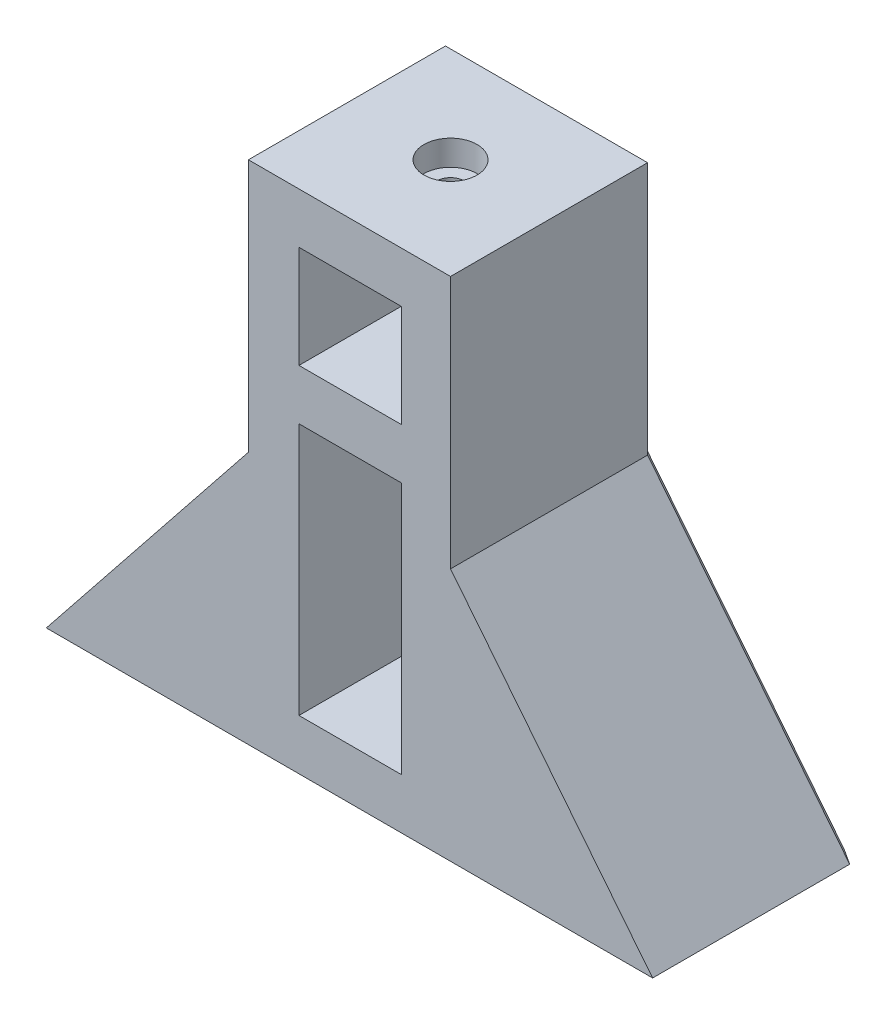
SolidWorks part; units mm, degrees
ref_plane "Front Plane" through (0, 0, 0) normal (0, 0, 1) x (1, 0, 0)
ref_plane "Top Plane" through (0, 0, 0) normal (0, 1, 0) x (1, 0, 0)
ref_plane "Right Plane" through (0, 0, 0) normal (1, 0, 0) x (0, 0, -1)
sketch "Sketch1" plane through (0, 0, 0) normal (0, 0, 1) x (1, 0, 0)
  line L0 (0, 46) -> (0, -105.2189) construction
  line L1 (-67.6667, 0) -> (81.3333, 0) construction
  line L2 (20, -19.875) -> (60, -70)
  line L3 (-10, 20.25) -> (10.25, 20.25)
  line L4 (-10, 20.25) -> (-10, 0)
  line L5 (-10, 0) -> (10.25, 0)
  line L6 (10.25, 20.25) -> (10.25, 0)
  line L7 (-20, 30.25) -> (20, 30.25)
  line L8 (-20, 30.25) -> (-20, -19.875)
  line L9 (-20, -70) -> (20, -70)
  line L10 (20, 30.25) -> (20, -19.875)
  line L23 (60, -70) -> (20, -70)
  line L24 (-60, -70) -> (-20, -70)
  line L25 (-20, -19.875) -> (-60, -70)
  line L27 (-10, -10) -> (10.25, -10)
  line L28 (-10, -10) -> (-10, -60)
  line L29 (-10, -60) -> (10.25, -60)
  line L30 (10.25, -10) -> (10.25, -60)
  dimension "D1" = 20.25
  dimension "D2" = 20.25
  dimension "D3" = 10.25
  dimension "D4" = 10
  dimension "D5" = 40
  dimension "D6" = 20
  dimension "D7" = 70
  dimension "D8" = 60
  dimension "D9" = 50
  dimension "D10" = 10
  dimension "D11" = 20.25
extrude "Boss-Extrude1" add sketch "Sketch1" along normal blind 40
chamfer "Chamfer1" distance 1 angle 45 14 edges at (0.125, 20.25, 0) (10.25, 10.125, 0) (0.125, 0, 0) (-10, 10.125, 0) (0, -70, 0) (20, 5.1875, 0) (0, 30.25, 0) (-20, 5.1875, 0) (-40, -44.9375, 0) (40, -44.9375, 0) (0.125, -10, 0) (10.25, -35, 0) (0.125, -60, 0) (-10, -35, 0)
sketch "Sketch2" plane through (0, 30.25, 0) normal (0, 1, 0) x (1, 0, 0)
  line L0 (-20, -40) -> (-20, -1) construction
  circle A0 centre (0, -20) radius 2.75
  dimension "D1" = 5.5
  dimension "D3" = 20
  dimension "D2" = 20
extrude "Cut-Extrude1" cut sketch "Sketch2" against normal blind 20
sketch "Sketch3" plane through (0, 30.25, 0) normal (0, 1, 0) x (1, 0, 0)
  circle A0 centre (0, -20) radius 5.25
  dimension "D1" = 10.5
extrude "Cut-Extrude2" cut sketch "Sketch3" against normal blind 5
